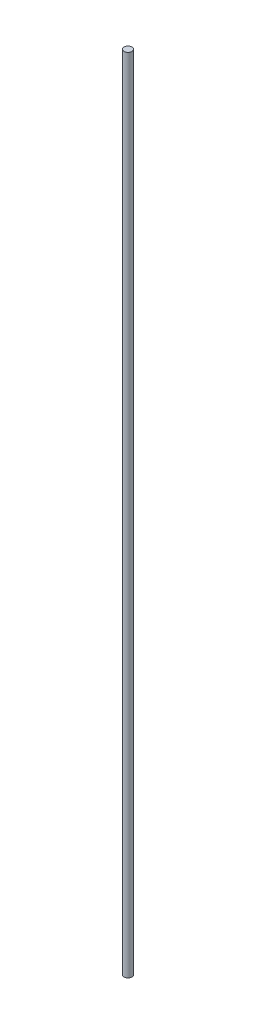
SolidWorks part; units mm, degrees
material "AISI 1020"
ref_plane "Front Plane" through (0, 0, 0) normal (0, 0, 1) x (1, 0, 0)
ref_plane "Top Plane" through (0, 0, 0) normal (0, 1, 0) x (1, 0, 0)
ref_plane "Right Plane" through (0, 0, 0) normal (1, 0, 0) x (0, 0, -1)
sketch "Sketch1" plane through (0, 0, 0) normal (0, 1, 0) x (1, 0, 0)
  circle A0 centre (0, 0) radius 4
  dimension "D1" = 8
extrude "Boss-Extrude1" add sketch "Sketch1" along normal blind 420 and the other way blind 400
cosmetic thread "Cosmetic Thread1" parameters "D2"=7
